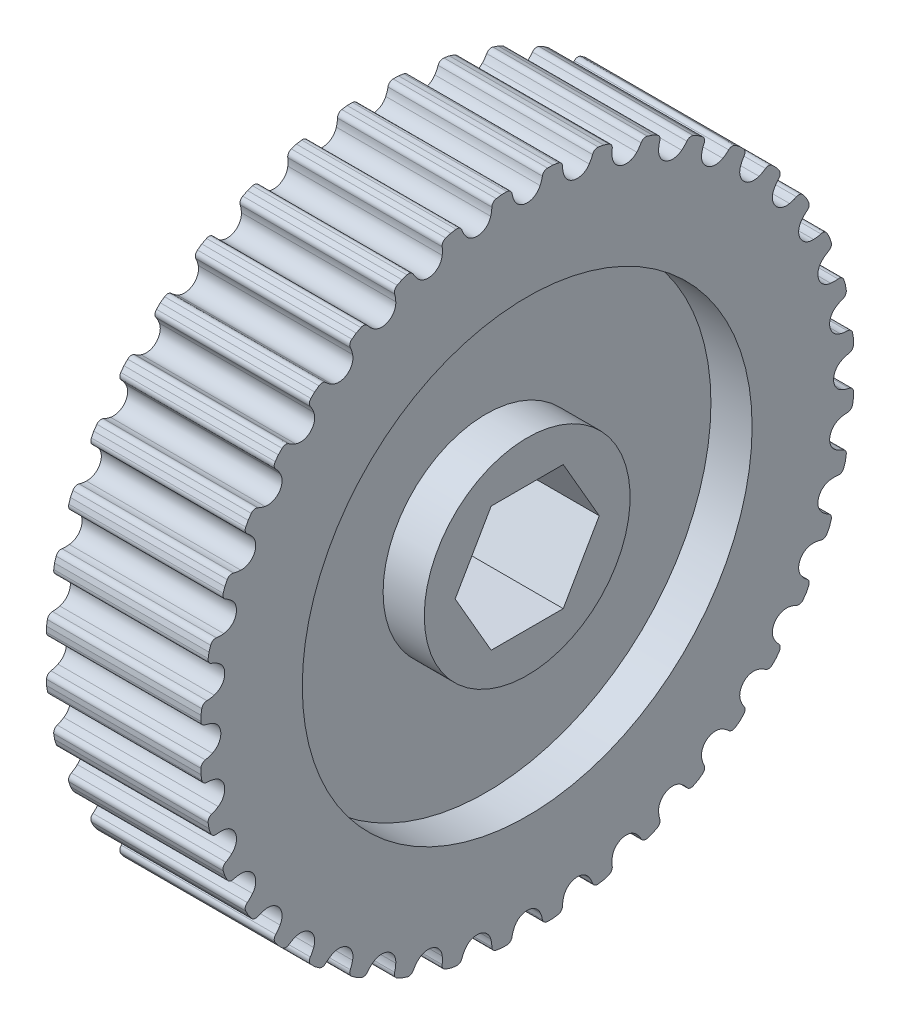
SolidWorks part; units mm, degrees
material "6061 Alloy"
ref_plane "Front Plane" through (0, 0, 0) normal (0, 0, 1) x (1, 0, 0)
ref_plane "Top Plane" through (0, 0, 0) normal (0, 1, 0) x (1, 0, 0)
ref_plane "Right Plane" through (0, 0, 0) normal (1, 0, 0) x (0, 0, -1)
sketch "Sketch1" plane through (0, 0, 0) normal (0, 0, 1) x (1, 0, 0)
  line L0 (-151.2927, -11.5093) -> (0, -11.5093) construction
  line L1 (-74.7494, -11.5093) -> (-74.7494, -1.5093)
  line L2 (-74.7494, -1.5093) -> (-78.7494, -1.5093)
  line L3 (-78.7494, -1.5093) -> (-78.7494, 10.3407)
  line L4 (-78.7494, 10.3407) -> (-74.7494, 10.3407)
  line L5 (-74.7494, 10.3407) -> (-74.7494, 20.3407)
  line L6 (-74.7494, 20.3407) -> (-89.7494, 20.3407)
  line L7 (-89.7494, 20.3407) -> (-89.7494, 10.3407)
  line L8 (-89.7494, 10.3407) -> (-85.7494, 10.3407)
  line L9 (-85.7494, 10.3407) -> (-85.7494, -1.5093)
  line L10 (-85.7494, -1.5093) -> (-89.7494, -1.5093)
  line L11 (-89.7494, -1.5093) -> (-89.7494, -11.5093)
  line L12 (-89.7494, -11.5093) -> (-74.7494, -11.5093)
  dimension "D1" = 31.85
  dimension "D2" = 10
  dimension "D3" = 15
  dimension "D4" = 4
  dimension "D5" = 10
revolve "Revolve1" add sketch "Sketch1" angle 360 about L0
sketch "Sketch2" plane through (-89.7494, 0, 0) normal (-1, 0, 0) x (0, 0, 1)
  line L1 (7, -11.5762) -> (3.5, -5.5141)
  line L8 (3.5, -5.5141) -> (-3.5, -5.5141)
  line L9 (-3.5, -5.5141) -> (-7, -11.5762)
  line L10 (-7, -11.5762) -> (-3.5, -17.6384)
  line L11 (-3.5, -17.6384) -> (3.5, -17.6384)
  line L12 (3.5, -17.6384) -> (7, -11.5762)
  circle A2 centre (0, -11.5762) radius 6.0622 construction
  dimension "D1" = 7
extrude "Cut-Extrude1" cut sketch "Sketch2" against normal blind 20
sketch "Sketch3" plane through (-89.7494, 0, 0) normal (-1, 0, 0) x (0, 0, 1)
  line L0 (0, -69.3619) -> (0, 130.6381) construction
  line L1 (-1.9771, 20.1859) -> (-2.5, 20.1859)
  line L2 (0, 20.1859) -> (0, 18.2559) construction
  line L3 (0, 18.2559) -> (0, 19.6259) construction
  line L4 (0, 20.1859) -> (1.03, 20.1859) construction
  line L5 (-2.5, 20.1859) -> (-2.5, 22.0559)
  line L6 (-2.5, 22.0559) -> (2.5, 22.0559)
  line L7 (2.5, 20.1859) -> (2.5, 22.0559)
  line L8 (1.9771, 20.1859) -> (2.5, 20.1859)
  arc A0 (1.2559, 19.0785) -> (-1.2559, 19.0785) centre (0, 19.6259) cw
  arc A1 (1.2559, 19.0785) -> (1.4742, 19.7611) centre (-1.03, 20.1859) ccw
  arc A2 (-1.4742, 19.7611) -> (-1.9771, 20.1859) centre (-1.9771, 19.6759) ccw
  arc A3 (-1.2559, 19.0785) -> (-1.4742, 19.7611) centre (1.03, 20.1859) cw
  arc A4 (1.4742, 19.7611) -> (1.9771, 20.1859) centre (1.9771, 19.6759) cw
  point P21 (0, 22.0559)
  dimension "D3" = 2.54
  dimension "D1" = 0.51
  dimension "D2" = 1.37
extrude "Cut-Extrude2" cut sketch "Sketch3" against normal through all
pattern_circular "CirPattern1" count 40 every 9 about axis through (0, -11.5093, 0) along (1, 0, 0) of "Cut-Extrude2"
